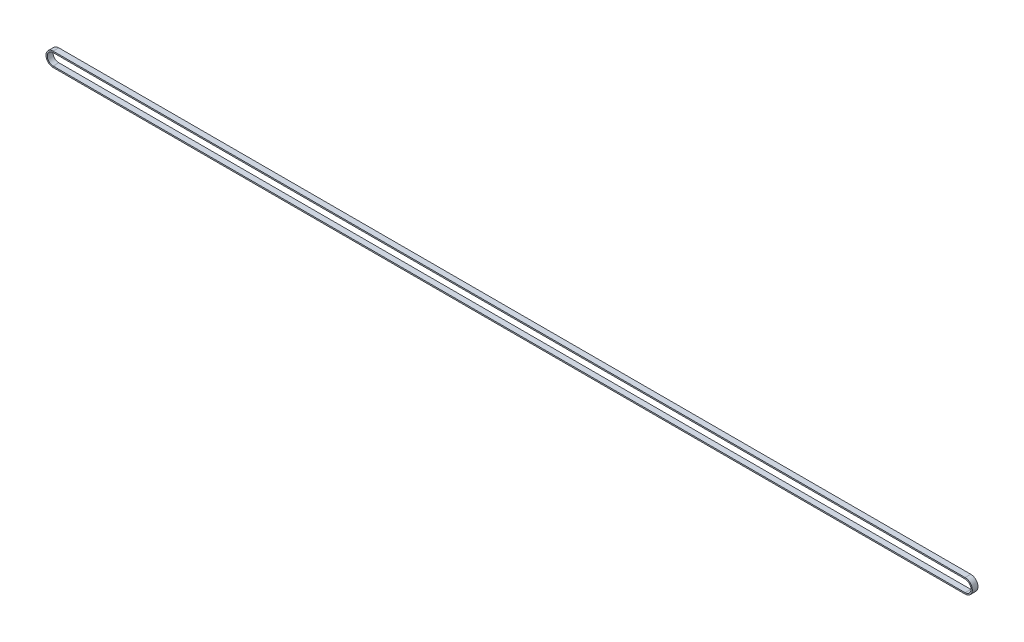
SolidWorks part; units mm, degrees
ref_plane "Front Plane" through (0, 0, 0) normal (0, 0, 1) x (1, 0, 0)
ref_plane "Top Plane" through (0, 0, 0) normal (0, 1, 0) x (1, 0, 0)
ref_plane "Right Plane" through (0, 0, 0) normal (1, 0, 0) x (0, 0, -1)
sketch "Sketch2" plane through (0, 0, 0) normal (0, 0, 1) x (1, 0, 0)
  line L0 (0, 0) -> (1, 0) construction
  line L1 (0, 0) -> (0, 1) construction
  line L2 (-0.0008, 7.49) -> (960.9835, 7.59)
  line L3 (960.9835, -7.59) -> (-0.0008, -7.49)
  line L4 (960.9836, -6.21) -> (-0.0006, -6.11)
  line L5 (-0.0006, 6.11) -> (960.9836, 6.21)
  arc A0 (-0.0006, -6.11) -> (-0.0006, 6.11) centre (0, 0) cw
  arc A1 (-0.0008, -7.49) -> (-0.0008, 7.49) centre (0, 0) cw
  arc A2 (960.9836, 6.21) -> (960.9836, -6.21) centre (960.9843, 0) cw
  arc A3 (960.9835, 7.59) -> (960.9835, -7.59) centre (960.9843, 0) cw
  dimension "D1" = 1.38
extrude "Boss-Extrude1" add sketch "Sketch2" along normal mid plane 6
